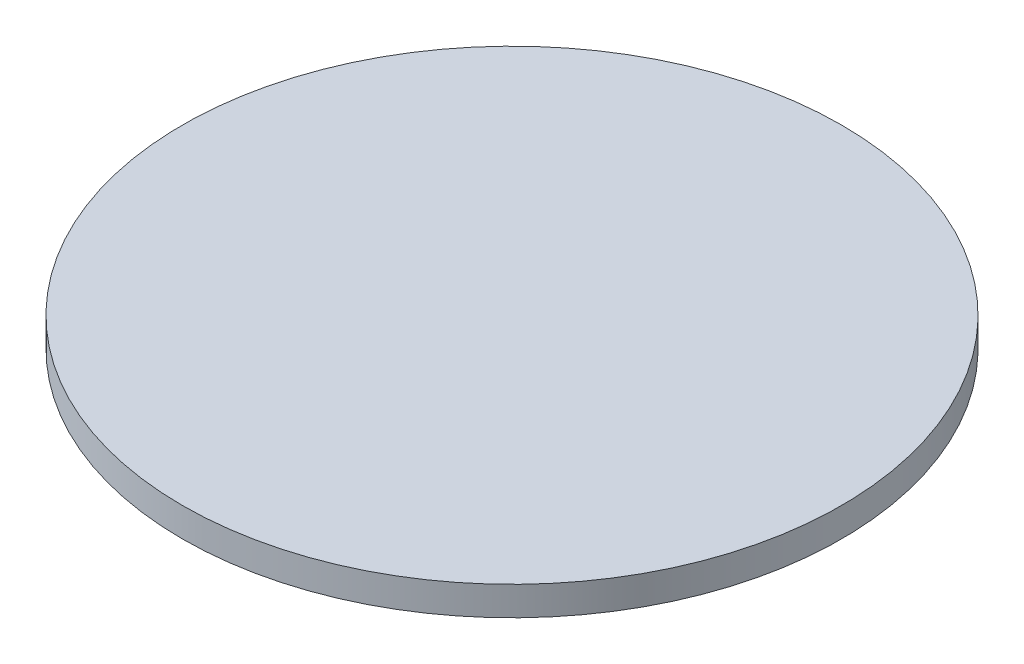
SolidWorks part; units mm, degrees
ref_plane "前视基准面" through (0, 0, 0) normal (0, 0, 1) x (1, 0, 0)
ref_plane "上视基准面" through (0, 0, 0) normal (0, 1, 0) x (1, 0, 0)
ref_plane "右视基准面" through (0, 0, 0) normal (1, 0, 0) x (0, 0, -1)
other "Configuration Table"
sketch "草图1" plane through (0, 0, 0) normal (0, 1, 0) x (1, 0, 0)
  line L1 (0, 0) -> (25, 0) construction
  line L2 (0, 0) -> (0, 25) construction
  line L3 (0, 25) -> (25, 25) construction
  line L4 (25, 0) -> (25, 25) construction
  line L5 (0, 0) -> (25, 25) construction
  line L6 (0, 25) -> (25, 0) construction
  circle A0 centre (12.5, 12.5) radius 12.5
  point P4 (12.5, 12.5)
  dimension "D1" = 25
  dimension "D2" = 25
extrude "凸台-拉伸1" add sketch "草图1" along normal blind 1.1
